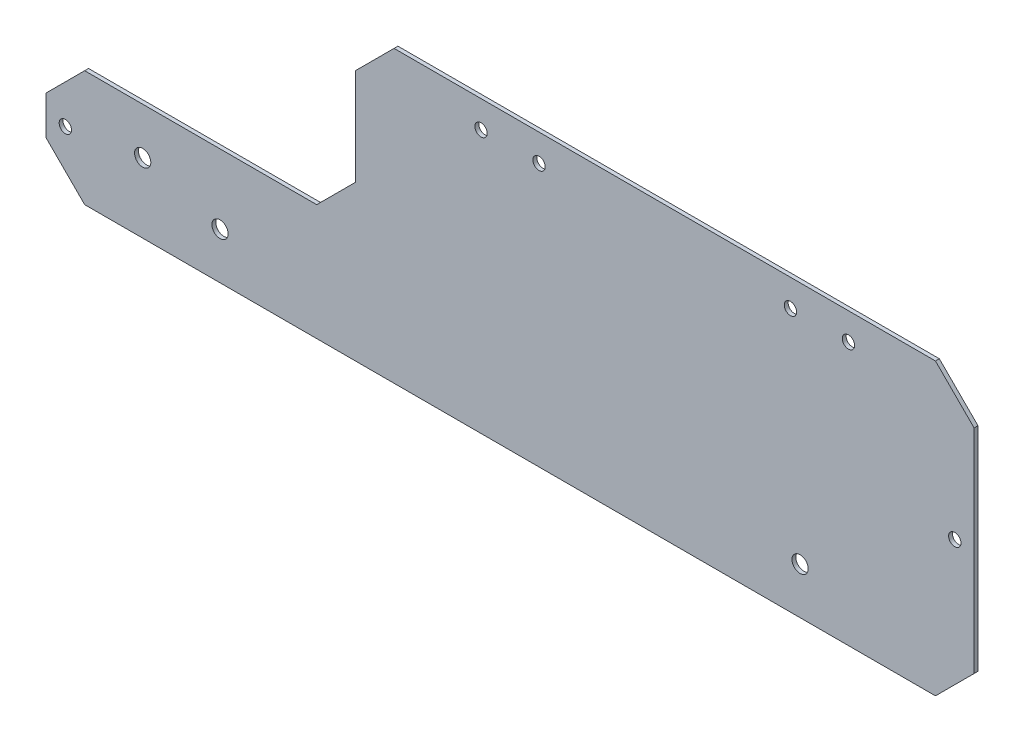
SolidWorks part; units mm, degrees
ref_plane "前视基准面" through (0, 0, 0) normal (0, 0, 1) x (1, 0, 0)
ref_plane "上视基准面" through (0, 0, 0) normal (0, 1, 0) x (1, 0, 0)
ref_plane "右视基准面" through (0, 0, 0) normal (1, 0, 0) x (0, 0, -1)
sketch "草图1" plane through (0, 0, 0) normal (0, 0, 1) x (1, 0, 0)
  line L0 (120, 0) -> (120, -120) construction
  line L1 (0, 0) -> (240, 0)
  line L2 (0, 0) -> (0, 75)
  line L3 (0, 75) -> (240, 75)
  line L4 (240, 0) -> (240, 75)
  line L5 (120, -120) -> (0, 0) construction
  line L6 (120, -120) -> (240, 0) construction
  line L7 (120, 75) -> (120, 0) construction
  dimension "D1" = 240
  dimension "D2" = 75
extrude "凸台-拉伸1" add sketch "草图1" along normal blind 1
sketch "草图3" plane through (0, 0, 0) normal (0, 0, -1) x (-1, 0, 0)
  line L0 (-120, 0) -> (-120, 75) construction
  line L1 (0, 0) -> (-240, 0) construction
  line L2 (-240, 75) -> (0, 75) construction
  line L4 (-100, 25) -> (-110, 42.3205)
  line L5 (-110, 42.3205) -> (-130, 42.3205)
  line L6 (-130, 42.3205) -> (-140, 25)
  line L7 (-140, 25) -> (-130, 7.6795)
  line L8 (-130, 7.6795) -> (-110, 7.6795)
  line L9 (-110, 7.6795) -> (-100, 25)
  circle A0 centre (-120, 25) radius 17.3205 construction
  dimension "D1" = 20
  dimension "D2" = 25
sketch "草图4" plane through (0, 0, 0) normal (0, 0, -1) x (-1, 0, 0)
  line L0 (-80, 75) -> (-80, 30)
  line L1 (-240, 75) -> (0, 75) construction
  line L2 (-80, 30) -> (0, 30)
  line L3 (0, 75) -> (0, 0) construction
  line L4 (0, 30) -> (0, 75)
  line L5 (0, 75) -> (-80, 75)
  dimension "D1" = 80
  dimension "D2" = 45
extrude "切除-拉伸3" cut sketch "草图4" against normal blind 10
chamfer "倒角1" distance 10 angle 45 6 edges at (80, 75, 0.5) (240, 75, 0.5) (0, 0, 0.5) (0, 30, 0.5) (80, 30, 0.5) (240, 0, 0.5)
sketch "草图5" plane through (0, 0, 0) normal (0, 0, -1) x (-1, 0, 0)
  line L0 (0, 15) -> (-5, 15) construction
  line L1 (0, 20) -> (0, 10) construction
  line L2 (-195, 12) -> (-45, 12) construction
  line L3 (-120, 0) -> (-120, 12) construction
  line L4 (-10, 0) -> (-230, 0) construction
  line L5 (-240, 37.5) -> (-235, 37.5) construction
  line L6 (-240, 10) -> (-240, 65) construction
  line L7 (-207.5, 68) -> (-192.5, 68) construction
  line L8 (-160, 75) -> (-160, 45) construction
  line L9 (-230, 75) -> (-90, 75) construction
  line L10 (-200, 68) -> (-200, 75) construction
  line L11 (-120, 68) -> (-120, 75) construction
  line L12 (-112.5, 68) -> (-127.5, 68) construction
  line L14 (-70, 30) -> (-10, 30) construction
  circle A0 centre (-5, 15) radius 1.6
  circle A1 centre (-195, 12) radius 2.1
  circle A2 centre (-45, 12) radius 2.1
  circle A3 centre (-235, 37.5) radius 1.6
  circle A4 centre (-207.5, 68) radius 1.6
  circle A5 centre (-192.5, 68) radius 1.6
  circle A6 centre (-127.5, 68) radius 1.6
  circle A7 centre (-112.5, 68) radius 1.6
  circle A8 centre (-25, 18) radius 2.1
  dimension "D2" = 3.2
  dimension "D4" = 4.2
  dimension "D7" = 3.2
  dimension "D10" = 3.2
  dimension "D1" = 5
  dimension "D3" = 150
  dimension "D5" = 12
  dimension "D6" = 5
  dimension "D8" = 30
  dimension "D9" = 15
  dimension "D11" = 7
  dimension "D12" = 40
  dimension "D13" = 20
  dimension "D14" = 12
extrude "切除-拉伸4" cut sketch "草图5" against normal blind 10
